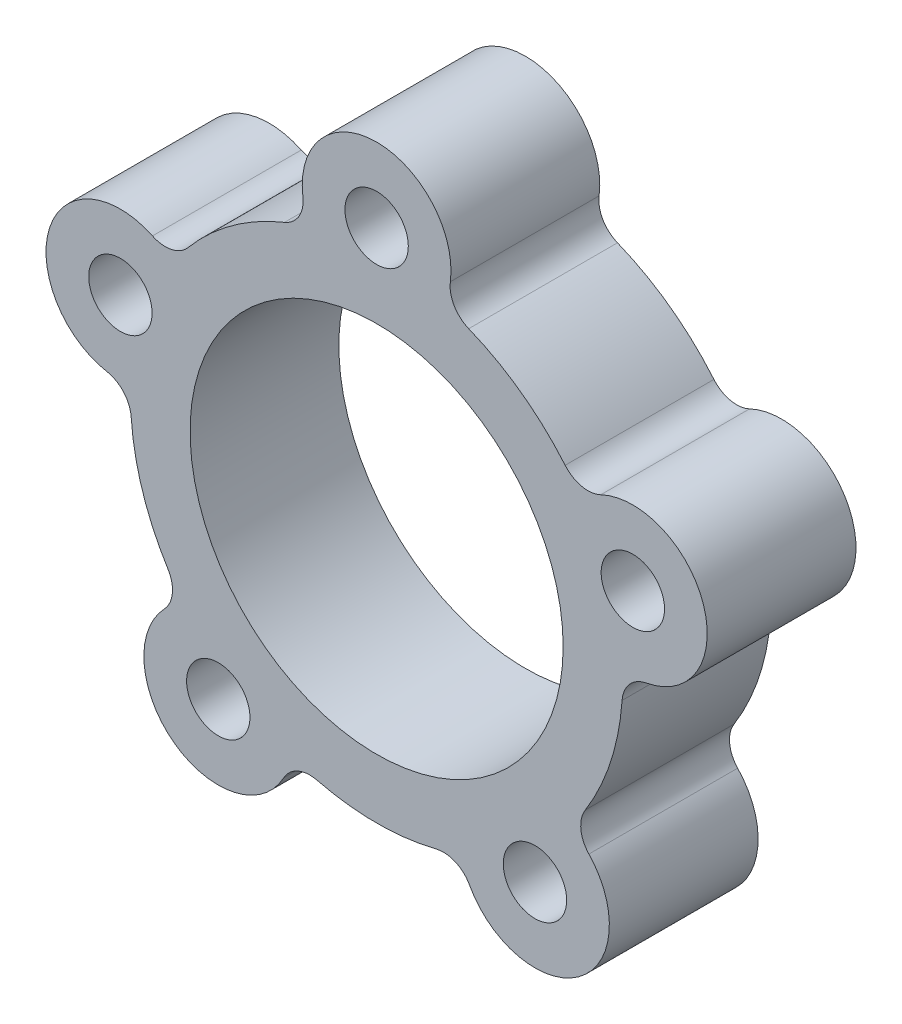
SolidWorks part; units mm, degrees
material "6061-T6 (SS)"
ref_plane "Front Plane" through (0, 0, 0) normal (0, 0, 1) x (1, 0, 0)
ref_plane "Top Plane" through (0, 0, 0) normal (0, 1, 0) x (1, 0, 0)
ref_plane "Right Plane" through (0, 0, 0) normal (1, 0, 0) x (0, 0, -1)
sketch "Sketch1" plane through (0, 0, 10.16) normal (0, 0, 1) x (1, 0, 0)
  circle A1 centre (0, 0) radius 7.9629
  circle A2 centre (0, 0) radius 7.9629
  arc A10 (8.0479, 6.7485) -> (3.9313, 9.7394) centre (0, 0) ccw
  arc A11 (3.1476, 11.0836) -> (-3.1476, 11.0836) centre (0, 11.5) ccw
  arc A12 (-3.9313, 9.7394) -> (-8.0479, 6.7485) centre (0, 0) ccw
  arc A13 (-9.5685, 6.4186) -> (-11.5138, 0.4315) centre (-10.9371, 3.5537) ccw
  arc A14 (-10.4776, -0.7292) -> (-8.9051, -5.5686) centre (0, 0) ccw
  arc A15 (-9.0612, -7.1167) -> (-3.9684, -10.817) centre (-6.7595, -9.3037) ccw
  arc A16 (-2.5442, -10.1901) -> (2.5442, -10.1901) centre (0, 0) ccw
  arc A17 (3.9684, -10.817) -> (9.0612, -7.1167) centre (6.7595, -9.3037) ccw
  arc A18 (8.9051, -5.5686) -> (10.4776, -0.7292) centre (0, 0) ccw
  arc A19 (11.5138, 0.4315) -> (9.5685, 6.4186) centre (10.9371, 3.5537) ccw
  arc A20 (8.0479, 6.7485) -> (3.9313, 9.7394) centre (0, 0) ccw
  arc A21 (3.1476, 11.0836) -> (-3.1476, 11.0836) centre (0, 11.5) ccw
  arc A22 (-3.9313, 9.7394) -> (-8.0479, 6.7485) centre (0, 0) ccw
  arc A23 (-9.5685, 6.4186) -> (-11.5138, 0.4315) centre (-10.9371, 3.5537) ccw
  arc A24 (-10.4776, -0.7292) -> (-8.9051, -5.5686) centre (0, 0) ccw
  arc A25 (-9.0612, -7.1167) -> (-3.9684, -10.817) centre (-6.7595, -9.3037) ccw
  arc A26 (-2.5442, -10.1901) -> (2.5442, -10.1901) centre (0, 0) ccw
  arc A27 (3.9684, -10.817) -> (9.0612, -7.1167) centre (6.7595, -9.3037) ccw
  arc A28 (8.9051, -5.5686) -> (10.4776, -0.7292) centre (0, 0) ccw
  arc A29 (11.5138, 0.4315) -> (9.5685, 6.4186) centre (10.9371, 3.5537) ccw
  arc A72 (8.0479, 6.7485) -> (9.5685, 6.4186) centre (9.0211, 7.5645) ccw
  arc A73 (8.0479, 6.7485) -> (9.5685, 6.4186) centre (9.0211, 7.5645) ccw
  arc A74 (3.1476, 11.0836) -> (3.9313, 9.7394) centre (4.4066, 10.9171) ccw
  arc A75 (3.1476, 11.0836) -> (3.9313, 9.7394) centre (4.4066, 10.9171) ccw
  arc A76 (-3.9313, 9.7394) -> (-3.1476, 11.0836) centre (-4.4066, 10.9171) ccw
  arc A77 (-3.9313, 9.7394) -> (-3.1476, 11.0836) centre (-4.4066, 10.9171) ccw
  arc A78 (-9.5685, 6.4186) -> (-8.0479, 6.7485) centre (-9.0211, 7.5645) ccw
  arc A79 (-9.5685, 6.4186) -> (-8.0479, 6.7485) centre (-9.0211, 7.5645) ccw
  arc A80 (-10.4776, -0.7292) -> (-11.5138, 0.4315) centre (-11.7445, -0.8174) ccw
  arc A81 (-10.4776, -0.7292) -> (-11.5138, 0.4315) centre (-11.7445, -0.8174) ccw
  arc A82 (-9.0612, -7.1167) -> (-8.9051, -5.5686) centre (-9.9819, -6.242) ccw
  arc A83 (-9.0612, -7.1167) -> (-8.9051, -5.5686) centre (-9.9819, -6.242) ccw
  arc A84 (-2.5442, -10.1901) -> (-3.9684, -10.817) centre (-2.8519, -11.4223) ccw
  arc A85 (-2.5442, -10.1901) -> (-3.9684, -10.817) centre (-2.8519, -11.4223) ccw
  arc A86 (3.9684, -10.817) -> (2.5442, -10.1901) centre (2.8519, -11.4223) ccw
  arc A87 (3.9684, -10.817) -> (2.5442, -10.1901) centre (2.8519, -11.4223) ccw
  arc A88 (8.9051, -5.5686) -> (9.0612, -7.1167) centre (9.9819, -6.242) ccw
  arc A89 (8.9051, -5.5686) -> (9.0612, -7.1167) centre (9.9819, -6.242) ccw
  arc A90 (11.5138, 0.4315) -> (10.4776, -0.7292) centre (11.7445, -0.8174) ccw
  arc A91 (11.5138, 0.4315) -> (10.4776, -0.7292) centre (11.7445, -0.8174) ccw
  dimension "D1" = 0
  dimension "D2" = 0
extrude "Boss-Extrude1" add sketch "Sketch1" along normal blind 6.35
sketch "Sketch4" plane through (0, 0, 16.51) normal (0, 0, 1) x (1, 0, 0)
  point P0 (-10.9371, 3.5537)
  point P3 (0, 11.5)
  point P6 (10.9371, 3.5537)
  point P9 (6.7595, -9.3037)
  point P12 (-6.7595, -9.3037)
hole_wizard "#6-32 Tapped Hole1" positions "Sketch4" profile "Sketch3" tap size "#6-32" standard "ANSI Inch" end condition through all
sketch "Sketch3" plane through (-10.9371, 3.5537, 16.51) normal (1, 0, 0) x (0, -1, 0)
  line L0 (0, 0) -> (0, 6.35)
  line L1 (0, 6.35) -> (1.3525, 6.35)
  line L2 (1.3525, 6.35) -> (1.3525, 0)
  line L5 (1.3525, 0) -> (0, 0)
  line L11 (0, -6.35) -> (0, 107.95) construction
  dimension "Thru Tap Drill Dia." = 2.7051
  dimension "Thru Tap Drill Depth" = 6.35
cosmetic thread "Hole Thread1" parameters "D2"=3.5052
cosmetic thread "Hole Thread2" parameters "D2"=3.5052
cosmetic thread "Hole Thread3" parameters "D2"=3.5052
cosmetic thread "Hole Thread4" parameters "D2"=3.5052
cosmetic thread "Hole Thread5" parameters "D2"=3.5052
